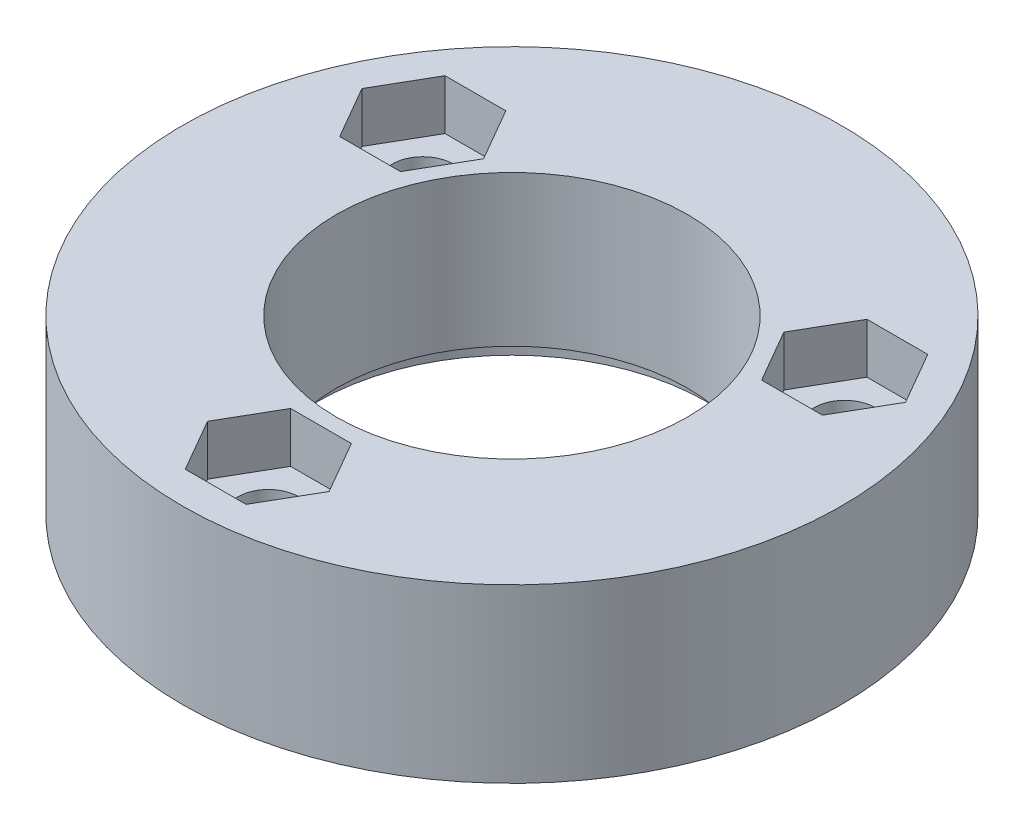
SolidWorks part; units mm, degrees
ref_plane "Front Plane" through (0, 0, 0) normal (0, 0, 1) x (1, 0, 0)
ref_plane "Top Plane" through (0, 0, 0) normal (0, 1, 0) x (1, 0, 0)
ref_plane "Right Plane" through (0, 0, 0) normal (1, 0, 0) x (0, 0, -1)
sketch "Sketch1" plane through (0, 0, 0) normal (0, 1, 0) x (1, 0, 0)
  circle A0 centre (0, 0) radius 12.25
  circle A1 centre (0, 0) radius 23
  dimension "D1" = 46
  dimension "D2" = 24.5
extrude "Boss-Extrude1" add sketch "Sketch1" along normal blind 12
sketch "Sketch2" plane through (0, 0, 0) normal (0, -1, 0) x (1, 0, 0)
  circle A0 centre (0, 0) radius 13.6
  dimension "D1" = 27.2
extrude "Cut-Extrude1" cut sketch "Sketch2" against normal blind 1.5
sketch "Sketch3" plane through (0, 12, 0) normal (0, 1, 0) x (1, 0, 0)
  circle A0 centre (0, -17) radius 2.125
  circle A1 centre (-14.7224, 8.5) radius 2.125
  circle A2 centre (14.7224, 8.5) radius 2.125
  point P9 (0, 0)
  dimension "D1" = 4.25
  dimension "D2" = 17
  dimension "D3" = 3
extrude "Cut-Extrude2" cut sketch "Sketch3" against normal through all
sketch "Sketch4" plane through (0, 12, 0) normal (0, 1, 0) x (1, 0, 0)
  line L0 (-16.8442, 4.825) -> (-12.6007, 4.825)
  line L1 (4.2435, -17) -> (2.1218, -13.325)
  line L2 (2.1218, -13.325) -> (-2.1218, -13.325)
  line L3 (-2.1218, -13.325) -> (-4.2435, -17)
  line L4 (-4.2435, -17) -> (-2.1218, -20.675)
  line L5 (-2.1218, -20.675) -> (2.1218, -20.675)
  line L6 (2.1218, -20.675) -> (4.2435, -17)
  line L7 (-18.966, 8.5) -> (-16.8442, 4.825)
  line L8 (-16.8442, 12.175) -> (-18.966, 8.5)
  line L9 (-12.6007, 12.175) -> (-16.8442, 12.175)
  line L10 (-10.4789, 8.5) -> (-12.6007, 12.175)
  line L11 (-12.6007, 4.825) -> (-10.4789, 8.5)
  line L12 (12.6007, 12.175) -> (10.4789, 8.5)
  line L13 (16.8442, 12.175) -> (12.6007, 12.175)
  line L14 (18.966, 8.5) -> (16.8442, 12.175)
  line L15 (16.8442, 4.825) -> (18.966, 8.5)
  line L16 (12.6007, 4.825) -> (16.8442, 4.825)
  line L17 (10.4789, 8.5) -> (12.6007, 4.825)
  circle A4 centre (0, -17) radius 3.675 construction
  point P10 (0, 0)
  point P28 (0, 0)
  dimension "D1" = 7.35
extrude "Cut-Extrude3" cut sketch "Sketch4" against normal blind 3.5
